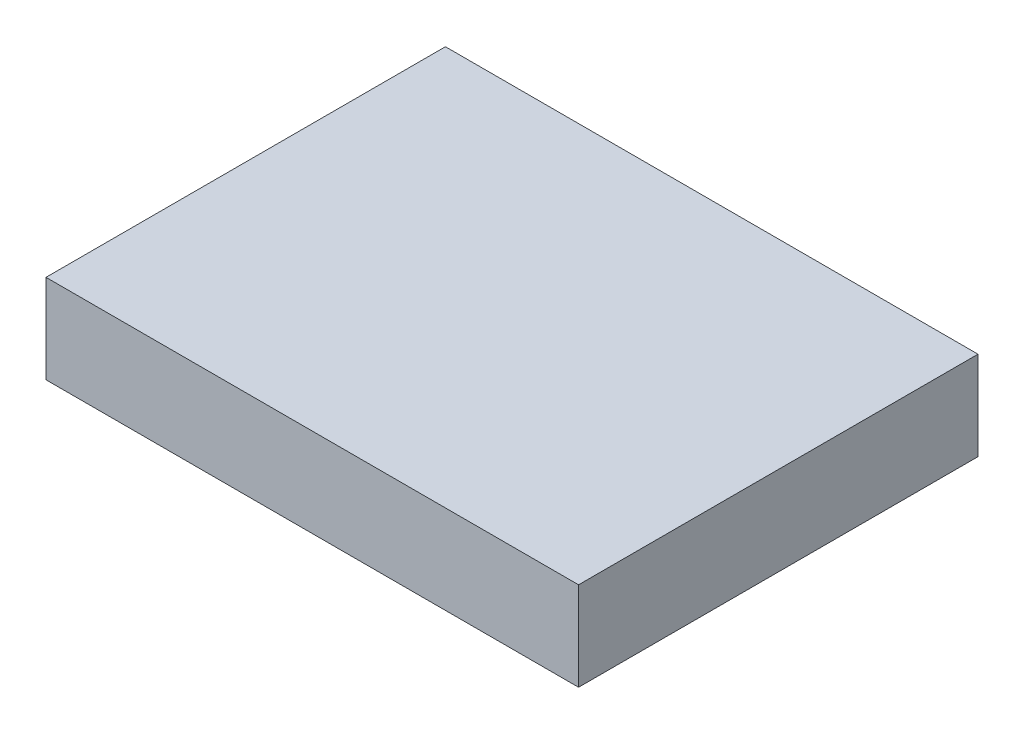
SolidWorks part; units mm, degrees
material "Maple"
ref_plane "Front Plane" through (0, 0, 0) normal (0, 0, 1) x (1, 0, 0)
ref_plane "Top Plane" through (0, 0, 0) normal (0, 1, 0) x (1, 0, 0)
ref_plane "Right Plane" through (0, 0, 0) normal (1, 0, 0) x (0, 0, -1)
sketch "Sketch1" plane through (0, 0, 0) normal (0, 1, 0) x (1, 0, 0)
  line L1 (30, 22.5) -> (-30, 22.5)
  line L2 (30, 22.5) -> (30, -22.5)
  line L3 (30, -22.5) -> (-30, -22.5)
  line L4 (-30, 22.5) -> (-30, -22.5)
  line L5 (30, 22.5) -> (-30, -22.5) construction
  line L6 (30, -22.5) -> (-30, 22.5) construction
  point P0 (0, 0)
  dimension "D1" = 45
  dimension "D2" = 60
extrude "Boss-Extrude1" add sketch "Sketch1" along normal blind 10
